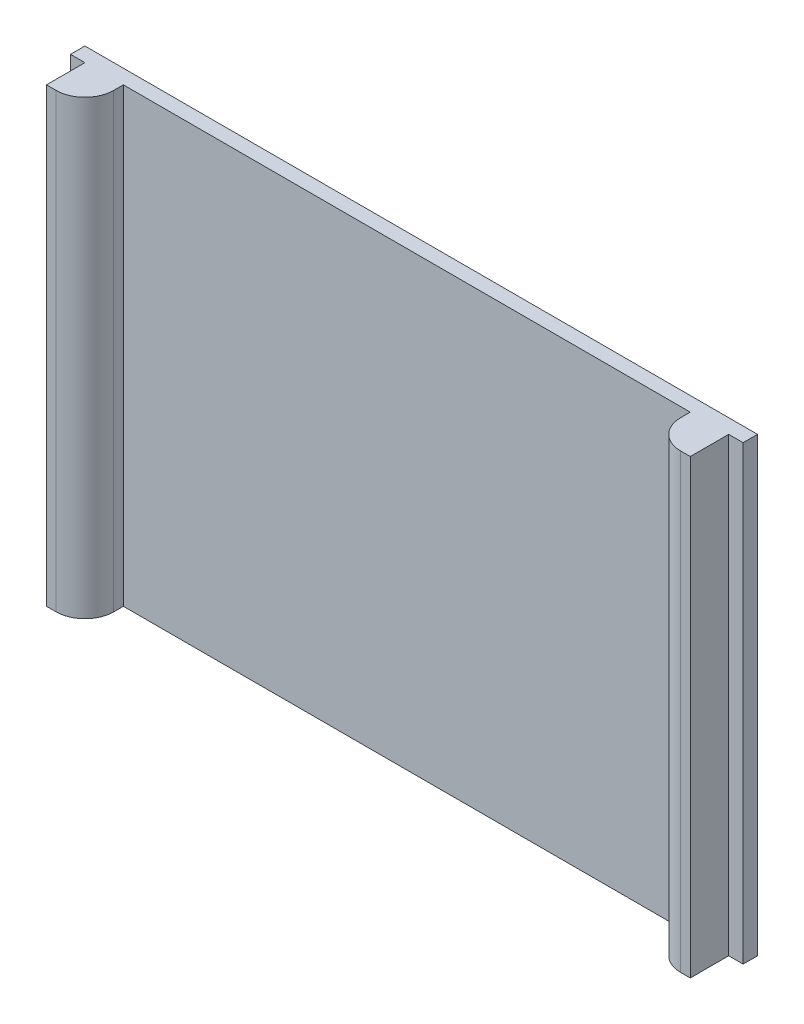
SolidWorks part; units mm, degrees
material "3.0205 (EN-AW 1200)"
ref_plane "Piano frontale" through (0, 0, 0) normal (0, 0, 1) x (1, 0, 0)
ref_plane "Piano superiore" through (0, 0, 0) normal (0, 1, 0) x (1, 0, 0)
ref_plane "Piano destro" through (0, 0, 0) normal (1, 0, 0) x (0, 0, -1)
sketch "Schizzo1" plane through (0, 0, 0) normal (0, 0, 1) x (1, 0, 0)
  line L1 (-350, -235) -> (350, -235)
  line L2 (-350, -235) -> (-350, 235)
  line L3 (-350, 235) -> (350, 235)
  line L4 (350, -235) -> (350, 235)
  line L5 (-350, -235) -> (350, 235) construction
  line L6 (-350, 235) -> (350, -235) construction
  point P0 (0, 0)
  dimension "D1" = 700
  dimension "D2" = 470
extrude "Estrusione-Estrusione1" add sketch "Schizzo1" along normal blind 15
sketch "Schizzo2" plane through (0, 0, 15) normal (0, 0, 1) x (1, 0, 0)
  line L0 (350, 235) -> (-350, 235) construction
  line L1 (-335, 235) -> (-295, 235)
  line L2 (-335, 235) -> (-335, -235)
  line L3 (-335, -235) -> (-295, -235)
  line L4 (-295, 235) -> (-295, -235)
  line L5 (-350, -235) -> (350, -235) construction
  line L6 (-350, 235) -> (-350, -235) construction
  dimension "D1" = 40
  dimension "D2" = 15
extrude "Estrusione-Estrusione2" add sketch "Schizzo2" along normal blind 40
fillet "Raccordo1" radius 30 1 edges at (-295, 0, 55)
mirror "Specchia1" about plane through (0, 0, 0) normal (1, 0, 0) of "Raccordo1", "Estrusione-Estrusione2"
